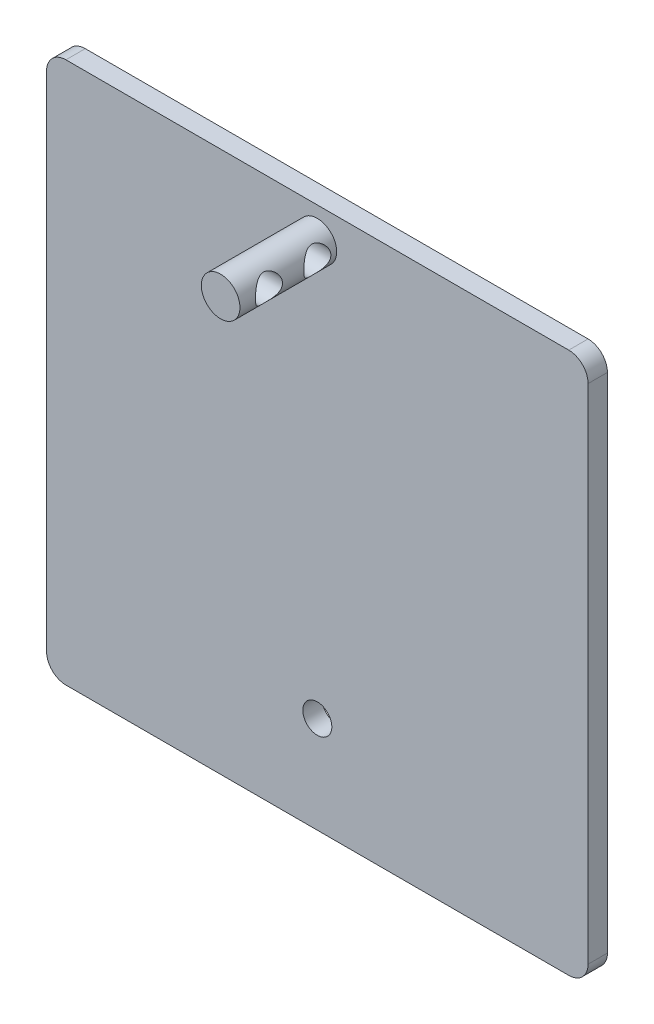
SolidWorks part; units mm, degrees
material "Balsa"
ref_plane "Front Plane" through (0, 0, 0) normal (0, 0, 1) x (1, 0, 0)
ref_plane "Top Plane" through (0, 0, 0) normal (0, 1, 0) x (1, 0, 0)
ref_plane "Right Plane" through (0, 0, 0) normal (1, 0, 0) x (0, 0, -1)
sketch "Sketch1" plane through (0, 0, 0) normal (0, 0, 1) x (1, 0, 0)
  line L1 (-130, -140) -> (130, -140)
  line L2 (-140, -130) -> (-140, 130)
  line L3 (-130, 140) -> (130, 140)
  line L4 (140, -130) -> (140, 130)
  line L5 (-140, -140) -> (140, 140) construction
  line L6 (-140, 140) -> (140, -140) construction
  arc A0 (-130, 140) -> (-140, 130) centre (-130, 130) ccw
  arc A1 (140, 130) -> (130, 140) centre (130, 130) ccw
  arc A2 (-130, -140) -> (-140, -130) centre (-130, -130) cw
  arc A3 (130, -140) -> (140, -130) centre (130, -130) ccw
  point P0 (0, 0)
  dimension "D3" = 10
  dimension "D4" = 10
  dimension "D5" = 10
  dimension "D6" = 10
  dimension "D1" = 280
  dimension "D2" = 280
extrude "Boss-Extrude1" add sketch "Sketch1" along normal blind 10
sketch "Sketch2" plane through (0, 0, 10) normal (0, 0, 1) x (1, 0, 0)
  line L0 (130, 140) -> (-130, 140) construction
  circle A0 centre (0, -90) radius 7.5
  dimension "D1" = 15
  dimension "D2" = 230
extrude "Cut-Extrude1" cut sketch "Sketch2" against normal through all
sketch "Sketch3" plane through (0, 0, 0) normal (0, 0, -1) x (-1, 0, 0)
  circle A2 centre (0, 124) radius 10
  dimension "D1" = 20
  dimension "D2" = 124
extrude "Boss-Extrude2" add sketch "Sketch3" against normal blind 60
sketch "Sketch5" plane through (0, 0, 0) normal (1, 0, 0) x (0, 0, -1)
  line L0 (-10, 134) -> (-60, 134) construction
  circle A0 centre (-20, 124) radius 7
  circle A1 centre (-45, 124) radius 7
  dimension "D4" = 14
  dimension "D5" = 14
  dimension "D1" = 10
  dimension "D2" = 45
  dimension "D3" = 20
extrude "Cut-Extrude3" cut sketch "Sketch5" against normal through all both and the other way through all
sketch "Sketch8" plane through (0, 0, 0) normal (0, 0, 1) x (1, 0, 0)
  text T0 "HACK ON" font "Century Gothic" height 10
extrude "Boss-Extrude3" add sketch "Sketch8" against normal blind 10
